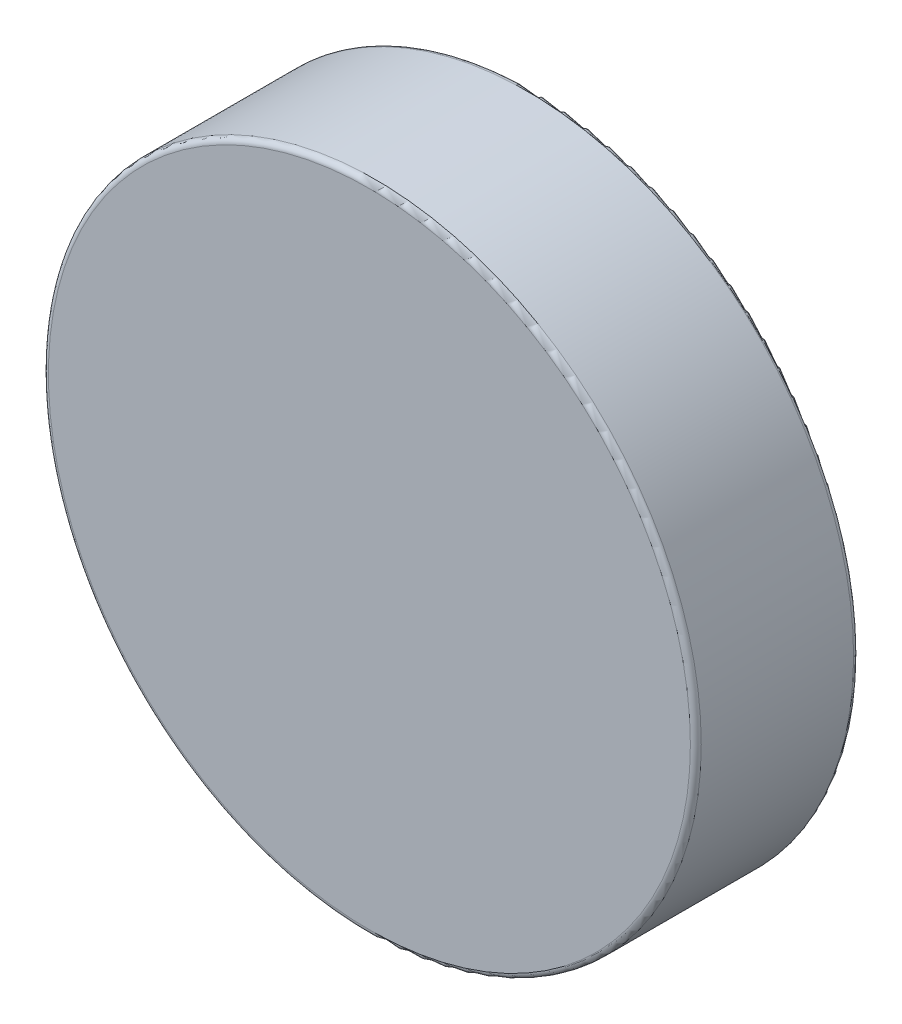
SolidWorks part; units mm, degrees
material "AISI 1020"
ref_plane "Front Plane" through (0, 0, 0) normal (0, 0, 1) x (1, 0, 0)
ref_plane "Top Plane" through (0, 0, 0) normal (0, 1, 0) x (1, 0, 0)
ref_plane "Right Plane" through (0, 0, 0) normal (1, 0, 0) x (0, 0, -1)
sketch "Sketch1" plane through (0, 0, 0) normal (0, 0, 1) x (1, 0, 0)
  circle A0 centre (0, 0) radius 30
  dimension "D1" = 60
extrude "Boss-Extrude1" add sketch "Sketch1" along normal mid plane 15
fillet "Fillet1" radius 0.5 2 edges at (30, 0, -7.5) (30, 0, 7.5)
